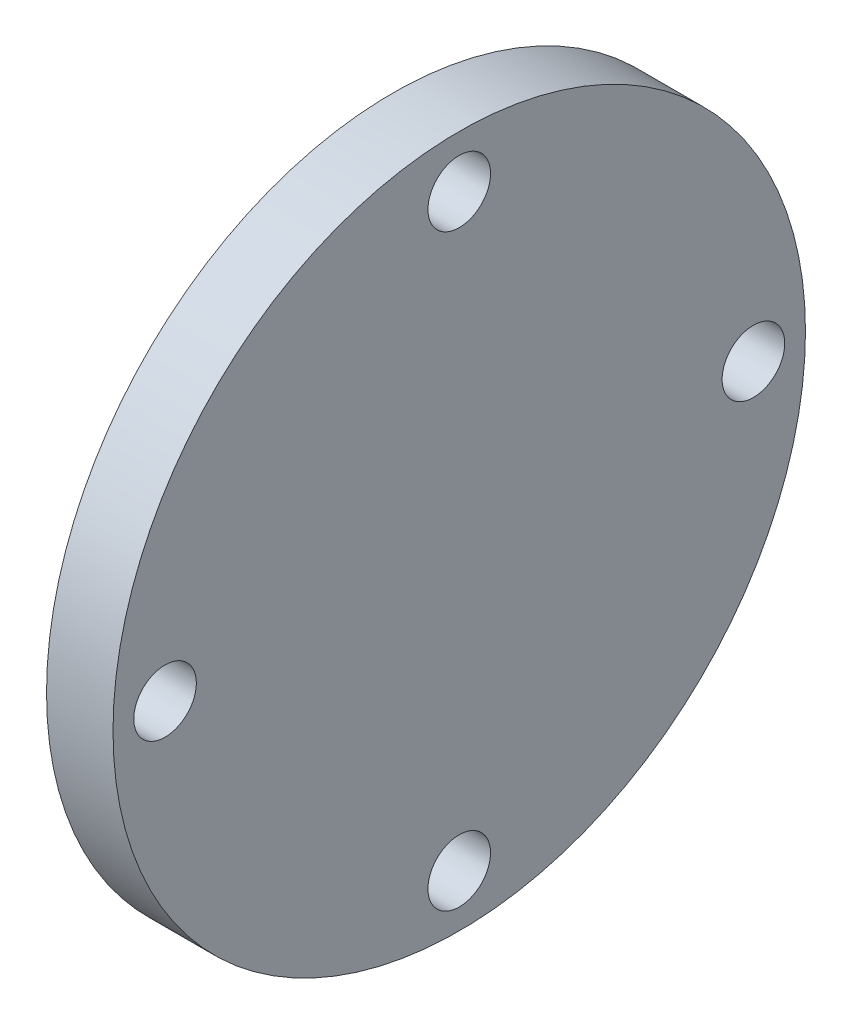
SolidWorks part; units mm, degrees
material "6061-T6 (SS)"
ref_plane "Front" through (0, 0, 0) normal (0, 0, 1) x (1, 0, 0)
ref_plane "Top" through (0, 0, 0) normal (0, 1, 0) x (1, 0, 0)
ref_plane "Right" through (0, 0, 0) normal (1, 0, 0) x (0, 0, -1)
sketch "Sketch1" plane through (0, 0, 0) normal (0, 0, 1) x (1, 0, 0)
  line L1 (0, 0) -> (0, 15.875)
  line L2 (0, 15.875) -> (-3.048, 15.875)
  line L3 (-3.048, 15.875) -> (-3.048, 11.1125)
  line L4 (-3.048, 11.1125) -> (-5.334, 11.1125)
  line L5 (-5.334, 11.1125) -> (-5.334, 0)
  line L6 (-5.334, 0) -> (0, 0)
  line L8 (0, 0) -> (-13.5095, 0) construction
  dimension "D1" = 3.048
  dimension "D2" = 2.286
  dimension "D3" = 22.225
  dimension "D4" = 31.75
revolve "Revolve1" add sketch "Sketch1" angle 360 about L8
sketch "Sketch2" plane through (0, 0, 0) normal (1, 0, 0) x (0, 0, -1)
  line L0 (-13.4874, 0) -> (13.4874, 0) construction
  line L1 (0, 13.4874) -> (0, -13.4874) construction
  circle A0 centre (0, 0) radius 13.4874 construction
  circle A1 centre (0, 13.4874) radius 1.4351
  circle A2 centre (13.4874, 0) radius 1.4351
  circle A3 centre (0, -13.4874) radius 1.4351
  circle A4 centre (-13.4874, 0) radius 1.4351
  dimension "D1" = 2.8702
  dimension "D2" = 13.4874
extrude "Cut-Extrude1" cut sketch "Sketch2" against normal through all
sketch "Sketch3" plane through (0, 0, 0) normal (1, 0, 0) x (0, 0, -1)
  circle A0 centre (0, 0) radius 5.0974
extrude "Cut-Extrude2" [suppressed] cut sketch "Sketch3" against normal through all
